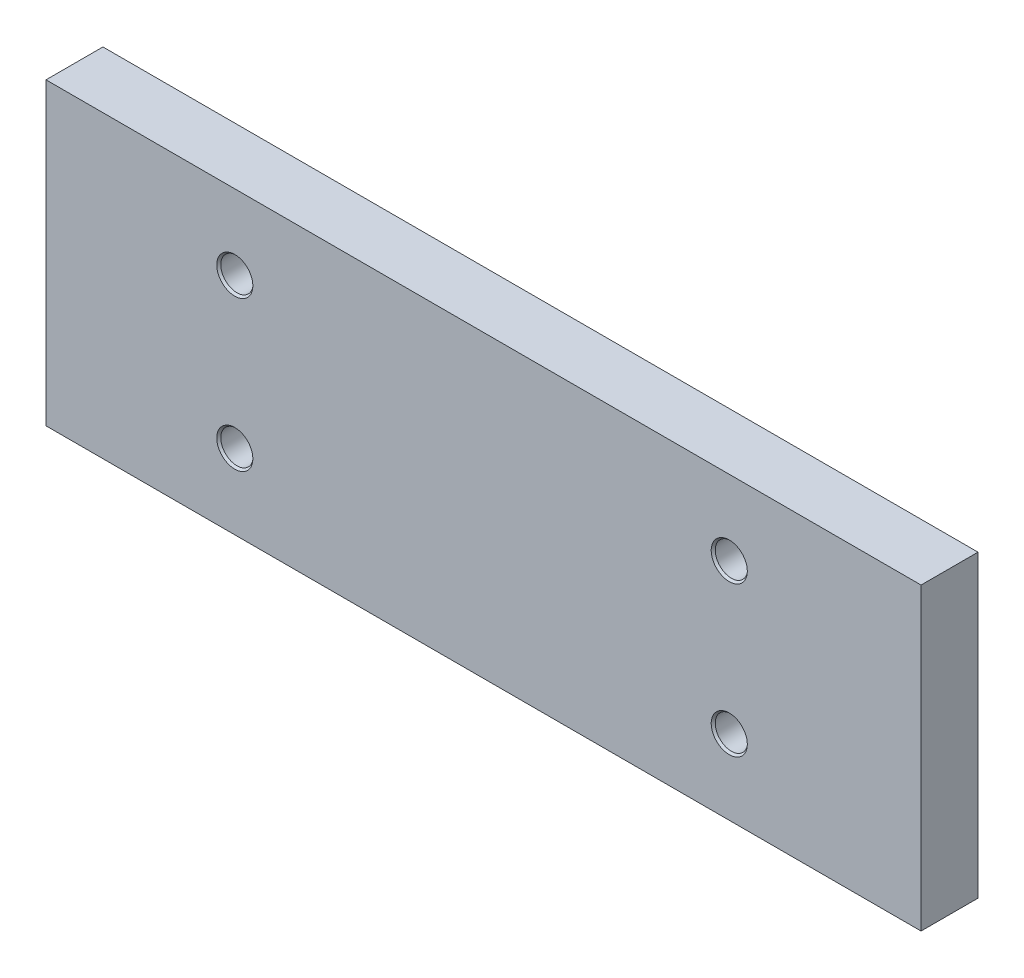
SolidWorks part; units mm, degrees
ref_plane "Piano frontale" through (0, 0, 0) normal (0, 0, 1) x (1, 0, 0)
ref_plane "Piano superiore" through (0, 0, 0) normal (0, 1, 0) x (1, 0, 0)
ref_plane "Piano destro" through (0, 0, 0) normal (1, 0, 0) x (0, 0, -1)
sketch "Schizzo1" plane through (0, 0, 0) normal (0, 0, 1) x (1, 0, 0)
  line L0 (-114.7929, 45.2663) -> (-114.7929, -54.7337)
  line L1 (-114.7929, -54.7337) -> (177.2071, -54.7337)
  line L2 (177.2071, -54.7337) -> (177.2071, 45.2663)
  line L3 (177.2071, 45.2663) -> (-114.7929, 45.2663)
  dimension "D1" = 100
  dimension "D2" = 292
extrude "Estrusione-Estrusione1" add sketch "Schizzo1" along normal blind 19
sketch "Schizzo2" plane through (0, 0, 19) normal (0, 0, 1) x (1, 0, 0)
  line L0 (177.2071, 45.2663) -> (-114.7929, 45.2663) construction
  line L1 (-51.7929, 20.2663) -> (113.2071, 20.2663) construction
  line L2 (-51.7929, 20.2663) -> (-51.7929, -29.7337) construction
  line L3 (-51.7929, -29.7337) -> (113.2071, -29.7337) construction
  line L4 (113.2071, 20.2663) -> (113.2071, -29.7337) construction
  line L5 (-114.7929, 45.2663) -> (-114.7929, -54.7337) construction
  dimension "D1" = 25
  dimension "D2" = 50
  dimension "D3" = 165
  dimension "D4" = 63
hole_wizard "Foro filettato M12x1.25-1" positions "Schizzo3D2" profile "Schizzo4" tap size "M12x1.25" standard "Ansi Metric" end condition through all
sketch3d "Schizzo3D2"
  point P0 (-51.7929, 20.2663, 19)
  point P3 (-51.7929, -29.7337, 19)
  point P6 (113.2071, -29.7337, 19)
  point P9 (113.2071, 20.2663, 19)
sketch "Schizzo4" plane through (-51.7929, 20.2663, 19) normal (1, 0, 0) x (0, -1, 0)
  line L0 (0, 0) -> (0, 19)
  line L1 (0, 19) -> (5.4, 19)
  line L2 (5.4, 19) -> (5.4, 0.719)
  line L3 (5.4, 0.719) -> (6.025, 0)
  line L5 (6.025, 0) -> (0, 0)
  line L6 (-5.4, 0.719) -> (-6.025, 0) construction
  line L11 (0, -6.35) -> (0, 107.95) construction
  dimension "Thru Tap Drill Dia." = 10.8
  dimension "Thru Tap Drill Depth" = 19
  dimension "Near C'Sink Dia." = 12.05
  dimension "Near C'Sink Angle" = 82
cosmetic thread "Filettatura del foro1" parameters "D2"=12
cosmetic thread "Filettatura del foro2" parameters "D2"=12
cosmetic thread "Filettatura del foro3" parameters "D2"=12
cosmetic thread "Filettatura del foro4" parameters "D2"=12
